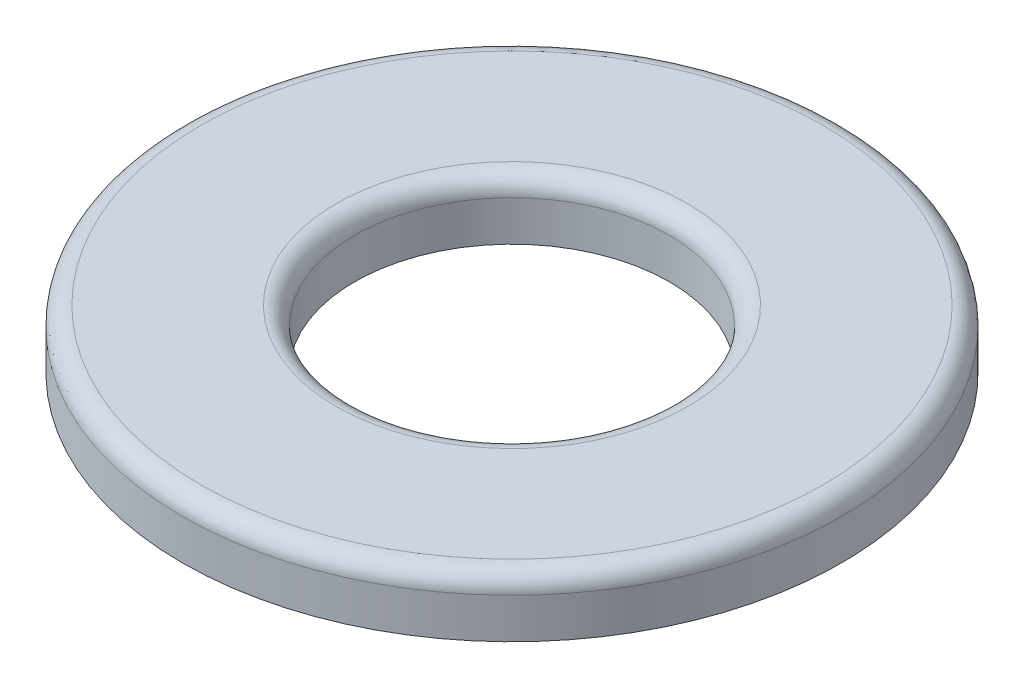
SolidWorks part; units mm, degrees
material "AISI Typ 316L stal nierdzewna"
ref_plane "Płaszczyzna przednia" through (0, 0, 0) normal (0, 0, 1) x (1, 0, 0)
ref_plane "Płaszczyzna górna" through (0, 0, 0) normal (0, 1, 0) x (1, 0, 0)
ref_plane "Płaszczyzna prawa" through (0, 0, 0) normal (1, 0, 0) x (0, 0, -1)
sketch "Szkic1" plane through (0, 0, 0) normal (0, 1, 0) x (1, 0, 0)
  circle A0 centre (0, 0) radius 4.5
  circle A1 centre (0, 0) radius 2.15
  dimension "D1" = 9
  dimension "4,3" = 4.3
extrude "Dodanie-wyciągnięcie1" add sketch "Szkic1" along normal blind 0.8
fillet "Zaokrąglenie1" radius 0.25 2 edges at (0, 0.8, 2.15) (0, 0.8, 4.5)
